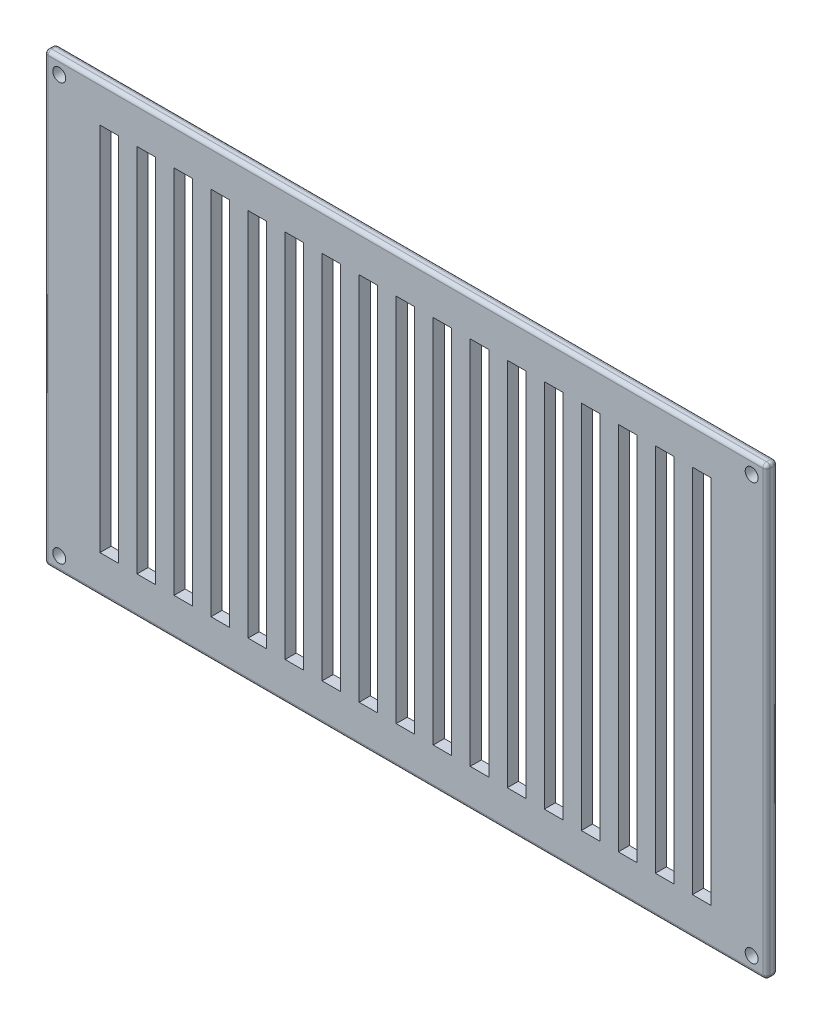
SolidWorks part; units mm, degrees
ref_plane "Front Plane" through (0, 0, 0) normal (0, 0, 1) x (1, 0, 0)
ref_plane "Top Plane" through (0, 0, 0) normal (0, 1, 0) x (1, 0, 0)
ref_plane "Right Plane" through (0, 0, 0) normal (1, 0, 0) x (0, 0, -1)
sketch "Sketch1" plane through (0, 0, 0) normal (0, 0, 1) x (1, 0, 0)
  line L0 (0, 116.54) -> (195, 116.54) construction
  line L1 (0, 0) -> (195, 0)
  line L2 (0, 0) -> (0, 120.54)
  line L3 (0, 120.54) -> (195, 120.54)
  line L4 (195, 0) -> (195, 120.54)
  line L5 (4, 120.54) -> (4, 0) construction
  line L6 (191, 120.54) -> (191, 0) construction
  line L7 (0, 4) -> (195, 4) construction
  circle A0 centre (4, 116.54) radius 1.75
  circle A1 centre (191, 116.54) radius 1.75
  circle A2 centre (4, 4) radius 1.75
  circle A3 centre (191, 4) radius 1.75
  dimension "D3" = 3.5
  dimension "D1" = 120.54
  dimension "D2" = 195
  dimension "D4" = 4
  dimension "D5" = 4
  dimension "D6" = 4
  dimension "D7" = 4
extrude "Boss-Extrude1" add sketch "Sketch1" along normal blind 3
fillet "Fillet1" radius 1 12 edges at (195, 60.27, 3) (195, 60.27, 0) (97.5, 0, 3) (195, 0, 1.5) (97.5, 0, 0) (195, 120.54, 1.5) (97.5, 120.54, 3) (97.5, 120.54, 0) (0, 120.54, 1.5) (0, 60.27, 3) (0, 0, 1.5) (0, 60.27, 0)
sketch "Sketch3" plane through (0, 0, 3) normal (0, 0, 1) x (1, 0, 0)
  line L0 (0, 60.27) -> (195, 60.27) construction
  line L1 (0, 1) -> (0, 119.54) construction
  line L2 (25, 10.27) -> (25, 110.27)
  line L3 (17.5, 120.54) -> (17.5, 0) construction
  line L4 (1, 120.54) -> (194, 120.54) construction
  line L5 (194, 0) -> (1, 0) construction
  line L6 (195, 119.54) -> (195, 1) construction
  line L7 (25, 10.27) -> (30, 10.27)
  line L8 (15, 10.27) -> (20, 10.27)
  line L9 (15, 10.27) -> (15, 110.27)
  line L10 (15, 110.27) -> (20, 110.27)
  line L11 (20, 10.27) -> (20, 110.27)
  line L12 (15, 10.27) -> (20, 110.27) construction
  line L13 (15, 110.27) -> (20, 10.27) construction
  line L14 (30, 10.27) -> (30, 110.27)
  line L15 (25, 110.27) -> (30, 110.27)
  line L16 (35, 10.27) -> (35, 110.27)
  line L17 (35, 10.27) -> (40, 10.27)
  line L18 (40, 10.27) -> (40, 110.27)
  line L19 (35, 110.27) -> (40, 110.27)
  line L20 (45, 10.27) -> (45, 110.27)
  line L21 (45, 10.27) -> (50, 10.27)
  line L22 (50, 10.27) -> (50, 110.27)
  line L23 (45, 110.27) -> (50, 110.27)
  line L24 (55, 10.27) -> (55, 110.27)
  line L25 (55, 10.27) -> (60, 10.27)
  line L26 (60, 10.27) -> (60, 110.27)
  line L27 (55, 110.27) -> (60, 110.27)
  line L28 (65, 10.27) -> (65, 110.27)
  line L29 (65, 10.27) -> (70, 10.27)
  line L30 (70, 10.27) -> (70, 110.27)
  line L31 (65, 110.27) -> (70, 110.27)
  line L32 (75, 10.27) -> (75, 110.27)
  line L33 (75, 10.27) -> (80, 10.27)
  line L34 (80, 10.27) -> (80, 110.27)
  line L35 (75, 110.27) -> (80, 110.27)
  line L36 (85, 10.27) -> (85, 110.27)
  line L37 (85, 10.27) -> (90, 10.27)
  line L38 (90, 10.27) -> (90, 110.27)
  line L39 (85, 110.27) -> (90, 110.27)
  line L40 (95, 10.27) -> (95, 110.27)
  line L41 (95, 10.27) -> (100, 10.27)
  line L42 (100, 10.27) -> (100, 110.27)
  line L43 (95, 110.27) -> (100, 110.27)
  line L44 (105, 10.27) -> (105, 110.27)
  line L45 (105, 10.27) -> (110, 10.27)
  line L46 (110, 10.27) -> (110, 110.27)
  line L47 (105, 110.27) -> (110, 110.27)
  line L48 (115, 10.27) -> (115, 110.27)
  line L49 (115, 10.27) -> (120, 10.27)
  line L50 (120, 10.27) -> (120, 110.27)
  line L51 (115, 110.27) -> (120, 110.27)
  line L52 (125, 10.27) -> (125, 110.27)
  line L53 (125, 10.27) -> (130, 10.27)
  line L54 (130, 10.27) -> (130, 110.27)
  line L55 (125, 110.27) -> (130, 110.27)
  line L56 (135, 10.27) -> (135, 110.27)
  line L57 (135, 10.27) -> (140, 10.27)
  line L58 (140, 10.27) -> (140, 110.27)
  line L59 (135, 110.27) -> (140, 110.27)
  line L60 (145, 10.27) -> (145, 110.27)
  line L61 (145, 10.27) -> (150, 10.27)
  line L62 (150, 10.27) -> (150, 110.27)
  line L63 (145, 110.27) -> (150, 110.27)
  line L64 (155, 10.27) -> (155, 110.27)
  line L65 (155, 10.27) -> (160, 10.27)
  line L66 (160, 10.27) -> (160, 110.27)
  line L67 (155, 110.27) -> (160, 110.27)
  line L68 (165, 10.27) -> (165, 110.27)
  line L69 (165, 10.27) -> (170, 10.27)
  line L70 (170, 10.27) -> (170, 110.27)
  line L71 (165, 110.27) -> (170, 110.27)
  line L72 (175, 10.27) -> (175, 110.27)
  line L73 (175, 10.27) -> (180, 10.27)
  line L74 (180, 10.27) -> (180, 110.27)
  line L75 (175, 110.27) -> (180, 110.27)
  point P12 (17.5, 60.27)
  dimension "D1" = 17.5
  dimension "D2" = 5
  dimension "D3" = 100
  dimension "D4" = 17
extrude "Cut-Extrude1" cut sketch "Sketch3" against normal through all
